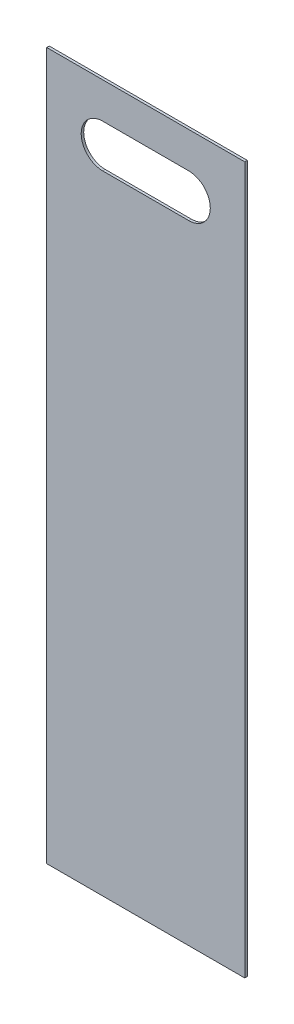
SolidWorks part; units mm, degrees
ref_plane "Front Plane" through (0, 0, 0) normal (0, 0, 1) x (1, 0, 0)
ref_plane "Top Plane" through (0, 0, 0) normal (0, 1, 0) x (1, 0, 0)
ref_plane "Right Plane" through (0, 0, 0) normal (1, 0, 0) x (0, 0, -1)
sketch "Sketch1" plane through (0, 0, 0) normal (0, 0, 1) x (1, 0, 0)
  line L0 (-10.9601, 32.766) -> (-10.9601, 45.466)
  line L1 (10.9601, 32.766) -> (-10.9601, 32.766) construction
  line L2 (10.9601, 32.766) -> (10.9601, -32.766)
  line L3 (10.9601, -32.766) -> (-10.9601, -32.766)
  line L4 (-10.9601, 32.766) -> (-10.9601, -32.766)
  line L5 (10.9601, 32.766) -> (-10.9601, -32.766) construction
  line L6 (10.9601, -32.766) -> (-10.9601, 32.766) construction
  line L7 (-10.9601, 45.466) -> (10.9601, 45.466)
  line L8 (10.9601, 45.466) -> (10.9601, 32.766)
  line L9 (4.7625, 39.116) -> (-4.7625, 39.116) construction
  line L10 (4.7625, 36.7348) -> (-4.7625, 36.7348)
  line L11 (4.7625, 41.4973) -> (-4.7625, 41.4973)
  line L12 (0, 39.116) -> (0, 0) construction
  arc A0 (4.7625, 36.7348) -> (4.7625, 41.4973) centre (4.7625, 39.116) ccw
  arc A1 (-4.7625, 41.4973) -> (-4.7625, 36.7348) centre (-4.7625, 39.116) ccw
  point P0 (0, 0)
  point P10 (0, 39.116)
  dimension "D1" = 65.532
  dimension "D2" = 21.9202
  dimension "D3" = 12.7
  dimension "D4" = 9.525
  dimension "D5" = 4.7625
  dimension "D6" = 6.35
extrude "Boss-Extrude1" add sketch "Sketch1" along normal blind 0.2794
equation "\"D1@Sketch1\" = 2.5 + .08"
equation "\"D2@Sketch1\"=\"oall_w\""
equation "\"space\" = 0.011"
equation "\"w\"= .745'width of the concentric ring into which it fits"
equation "\"in_cut\"= 0.07'length of cut into the wall"
equation "\"oall_w\"= \"w\" + 2 * \"in_cut\" - \"space\" * 2'overall width of spacer"
